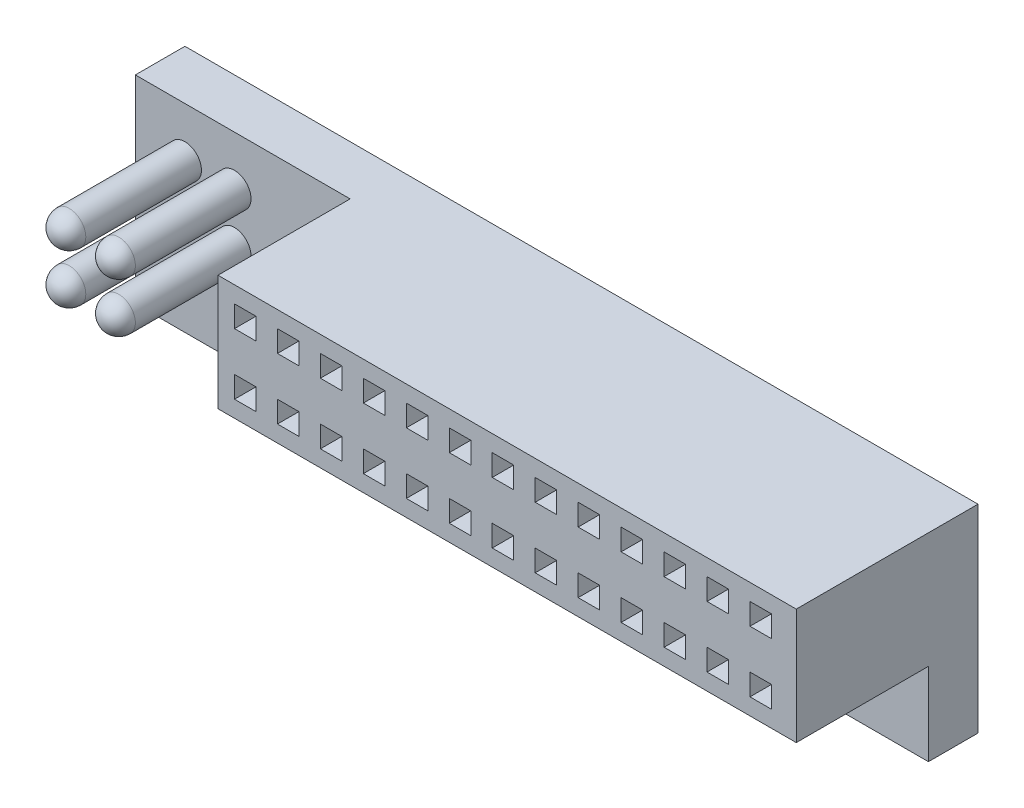
SolidWorks part; units mm, degrees
ref_plane "Front Plane" through (0, 0, 0) normal (0, 0, 1) x (1, 0, 0)
ref_plane "Top Plane" through (0, 0, 0) normal (0, 1, 0) x (1, 0, 0)
ref_plane "Right Plane" through (0, 0, 0) normal (1, 0, 0) x (0, 0, -1)
sketch "Sketch1" plane through (0, 0, 0) normal (0, 0, 1) x (1, 0, 0)
  line L1 (0, 0) -> (48, 0)
  line L2 (0, 0) -> (0, 12)
  line L3 (0, 12) -> (48, 12)
  line L4 (48, 0) -> (48, 12)
  dimension "D1" = 12
  dimension "D2" = 48
extrude "Boss-Extrude1" add sketch "Sketch1" along normal blind 3
sketch "Sketch2" plane through (0, 0, 3) normal (0, 0, 1) x (1, 0, 0)
  line L0 (16.6, 11) -> (17.9, 11)
  line L1 (48, 12) -> (13, 12)
  line L2 (48, 12) -> (48, 5)
  line L3 (48, 5) -> (13, 5)
  line L4 (13, 12) -> (13, 5)
  line L5 (14, 11) -> (15.3, 11)
  line L6 (14, 11) -> (14, 9.7)
  line L7 (14, 9.7) -> (15.3, 9.7)
  line L8 (15.3, 11) -> (15.3, 9.7)
  line L9 (14, 7.3) -> (15.3, 7.3)
  line L10 (14, 7.3) -> (14, 6)
  line L11 (14, 6) -> (15.3, 6)
  line L12 (15.3, 7.3) -> (15.3, 6)
  line L13 (17.9, 11) -> (17.9, 9.7)
  line L14 (16.6, 9.7) -> (17.9, 9.7)
  line L15 (16.6, 11) -> (16.6, 9.7)
  line L16 (16.6, 7.3) -> (17.9, 7.3)
  line L17 (17.9, 7.3) -> (17.9, 6)
  line L18 (16.6, 6) -> (17.9, 6)
  line L19 (16.6, 7.3) -> (16.6, 6)
  line L20 (19.2, 11) -> (20.5, 11)
  line L21 (20.5, 11) -> (20.5, 9.7)
  line L22 (19.2, 9.7) -> (20.5, 9.7)
  line L23 (19.2, 11) -> (19.2, 9.7)
  line L24 (19.2, 7.3) -> (20.5, 7.3)
  line L25 (20.5, 7.3) -> (20.5, 6)
  line L26 (19.2, 6) -> (20.5, 6)
  line L27 (19.2, 7.3) -> (19.2, 6)
  line L28 (21.8, 11) -> (23.1, 11)
  line L29 (23.1, 11) -> (23.1, 9.7)
  line L30 (21.8, 9.7) -> (23.1, 9.7)
  line L31 (21.8, 11) -> (21.8, 9.7)
  line L32 (21.8, 7.3) -> (23.1, 7.3)
  line L33 (23.1, 7.3) -> (23.1, 6)
  line L34 (21.8, 6) -> (23.1, 6)
  line L35 (21.8, 7.3) -> (21.8, 6)
  line L36 (24.4, 11) -> (25.7, 11)
  line L37 (25.7, 11) -> (25.7, 9.7)
  line L38 (24.4, 9.7) -> (25.7, 9.7)
  line L39 (24.4, 11) -> (24.4, 9.7)
  line L40 (24.4, 7.3) -> (25.7, 7.3)
  line L41 (25.7, 7.3) -> (25.7, 6)
  line L42 (24.4, 6) -> (25.7, 6)
  line L43 (24.4, 7.3) -> (24.4, 6)
  line L44 (27, 11) -> (28.3, 11)
  line L45 (28.3, 11) -> (28.3, 9.7)
  line L46 (27, 9.7) -> (28.3, 9.7)
  line L47 (27, 11) -> (27, 9.7)
  line L48 (27, 7.3) -> (28.3, 7.3)
  line L49 (28.3, 7.3) -> (28.3, 6)
  line L50 (27, 6) -> (28.3, 6)
  line L51 (27, 7.3) -> (27, 6)
  line L52 (29.6, 11) -> (30.9, 11)
  line L53 (30.9, 11) -> (30.9, 9.7)
  line L54 (29.6, 9.7) -> (30.9, 9.7)
  line L55 (29.6, 11) -> (29.6, 9.7)
  line L56 (29.6, 7.3) -> (30.9, 7.3)
  line L57 (30.9, 7.3) -> (30.9, 6)
  line L58 (29.6, 6) -> (30.9, 6)
  line L59 (29.6, 7.3) -> (29.6, 6)
  line L60 (32.2, 11) -> (33.5, 11)
  line L61 (33.5, 11) -> (33.5, 9.7)
  line L62 (32.2, 9.7) -> (33.5, 9.7)
  line L63 (32.2, 11) -> (32.2, 9.7)
  line L64 (32.2, 7.3) -> (33.5, 7.3)
  line L65 (33.5, 7.3) -> (33.5, 6)
  line L66 (32.2, 6) -> (33.5, 6)
  line L67 (32.2, 7.3) -> (32.2, 6)
  line L68 (34.8, 11) -> (36.1, 11)
  line L69 (36.1, 11) -> (36.1, 9.7)
  line L70 (34.8, 9.7) -> (36.1, 9.7)
  line L71 (34.8, 11) -> (34.8, 9.7)
  line L72 (34.8, 7.3) -> (36.1, 7.3)
  line L73 (36.1, 7.3) -> (36.1, 6)
  line L74 (34.8, 6) -> (36.1, 6)
  line L75 (34.8, 7.3) -> (34.8, 6)
  line L76 (37.4, 11) -> (38.7, 11)
  line L77 (38.7, 11) -> (38.7, 9.7)
  line L78 (37.4, 9.7) -> (38.7, 9.7)
  line L79 (37.4, 11) -> (37.4, 9.7)
  line L80 (37.4, 7.3) -> (38.7, 7.3)
  line L81 (38.7, 7.3) -> (38.7, 6)
  line L82 (37.4, 6) -> (38.7, 6)
  line L83 (37.4, 7.3) -> (37.4, 6)
  line L84 (40, 11) -> (41.3, 11)
  line L85 (41.3, 11) -> (41.3, 9.7)
  line L86 (40, 9.7) -> (41.3, 9.7)
  line L87 (40, 11) -> (40, 9.7)
  line L88 (40, 7.3) -> (41.3, 7.3)
  line L89 (41.3, 7.3) -> (41.3, 6)
  line L90 (40, 6) -> (41.3, 6)
  line L91 (40, 7.3) -> (40, 6)
  line L92 (42.6, 11) -> (43.9, 11)
  line L93 (43.9, 11) -> (43.9, 9.7)
  line L94 (42.6, 9.7) -> (43.9, 9.7)
  line L95 (42.6, 11) -> (42.6, 9.7)
  line L96 (42.6, 7.3) -> (43.9, 7.3)
  line L97 (43.9, 7.3) -> (43.9, 6)
  line L98 (42.6, 6) -> (43.9, 6)
  line L99 (42.6, 7.3) -> (42.6, 6)
  line L100 (45.2, 11) -> (46.5, 11)
  line L101 (46.5, 11) -> (46.5, 9.7)
  line L102 (45.2, 9.7) -> (46.5, 9.7)
  line L103 (45.2, 11) -> (45.2, 9.7)
  line L104 (45.2, 7.3) -> (46.5, 7.3)
  line L105 (46.5, 7.3) -> (46.5, 6)
  line L106 (45.2, 6) -> (46.5, 6)
  line L107 (45.2, 7.3) -> (45.2, 6)
  dimension "D3" = 1.3
  dimension "D1" = 7
  dimension "D2" = 35
  dimension "D4" = 1
  dimension "D5" = 1
  dimension "D6" = 1
  dimension "D8" = 1.3
  dimension "D7" = 13
extrude "Boss-Extrude2" add sketch "Sketch2" along normal blind 8
sketch "Sketch3" plane through (0, 0, 3) normal (0, 0, 1) x (1, 0, 0)
  line L0 (0, 0) -> (48, 0) construction
  line L1 (0, 12) -> (0, 0) construction
  circle A0 centre (3, 9) radius 1
  circle A1 centre (3, 6) radius 1
  circle A2 centre (6, 9) radius 1
  circle A3 centre (6, 6) radius 1
  point P8 (0, 0)
  point P9 (0, 0)
  point P10 (0, 0)
  point P11 (0, 0)
  point P14 (1.3155, 9)
  dimension "D1" = 2
  dimension "D2" = 3
  dimension "D3" = 3
  dimension "D4" = 6
  dimension "D5" = 3
extrude "Boss-Extrude3" add sketch "Sketch3" along normal blind 8
fillet "Fillet1" radius 1 4 edges at (4, 6, 11) (7, 6, 11) (7, 9, 11) (4, 9, 11)
